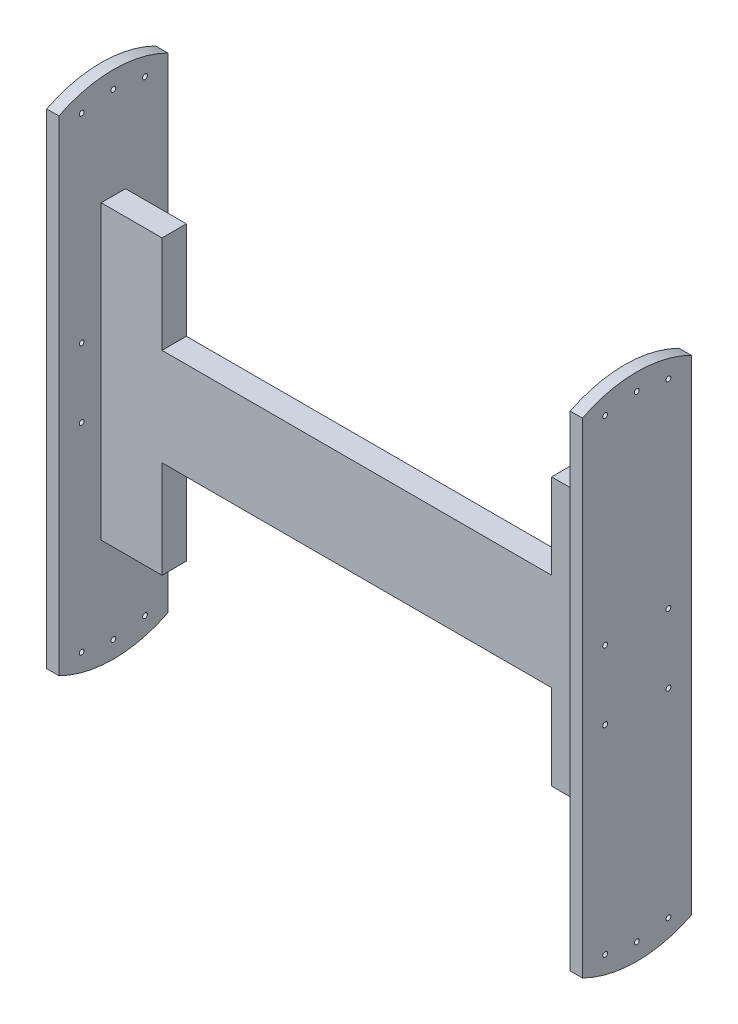
SolidWorks part; units mm, degrees
ref_plane "前视基准面" through (0, 0, 0) normal (0, 0, 1) x (1, 0, 0)
ref_plane "上视基准面" through (0, 0, 0) normal (0, 1, 0) x (1, 0, 0)
ref_plane "右视基准面" through (0, 0, 0) normal (1, 0, 0) x (0, 0, -1)
other "Configuration Table"
sketch "草图1" plane through (0, 0, 0) normal (0, 0, 1) x (1, 0, 0)
  line L1 (0, 0) -> (220, 0)
  line L2 (0, 0) -> (0, 120)
  line L3 (0, 120) -> (220, 120)
  line L4 (220, 0) -> (220, 120)
  dimension "D1" = 220
  dimension "D2" = 120
extrude "凸台-拉伸1" add sketch "草图1" along normal blind 10
sketch "草图2" plane through (0, 0, 10) normal (0, 0, 1) x (1, 0, 0)
  line L0 (0, 60) -> (220, 60) construction
  line L1 (0, 120) -> (0, 0) construction
  line L2 (220, 0) -> (220, 120) construction
  line L3 (30, 120) -> (30, 80)
  line L4 (220, 120) -> (0, 120) construction
  line L5 (30, 80) -> (190, 80)
  line L6 (190, 80) -> (190, 115)
  line L7 (190, 115) -> (220, 115)
  line L8 (190, 5) -> (220, 5)
  line L9 (190, 40) -> (190, 5)
  line L10 (30, 0) -> (30, 40)
  line L11 (30, 40) -> (190, 40)
  line L12 (0, 120) -> (0, 0)
  line L13 (0, 0) -> (220, 0)
  line L14 (220, 0) -> (220, 120)
  line L15 (220, 120) -> (0, 120)
  line L16 (0, 120) -> (0, 0)
  line L17 (0, 0) -> (220, 0)
  line L18 (220, 0) -> (220, 120)
  line L19 (220, 120) -> (0, 120)
  line M11 (0, 0) -> (220, 0)
  line M12 (220, 0) -> (220, 120)
  line M13 (220, 120) -> (0, 120)
  dimension "D1" = 0
  dimension "D2" = 30
  dimension "D3" = 30
  dimension "D4" = 5
  dimension "D5" = 20
extrude "切除-拉伸1" cut sketch "草图2" against normal blind 10 contours L6 L7 L3 L5 M12 M13 | L11 L10 L8 L9 M11 M12
sketch "草图5" plane through (220, 0, 0) normal (1, 0, 0) x (0, 0, -1)
  line L0 (-5, 115) -> (-5, 5) construction
  line L1 (-27.365, 70.4262) -> (-27.365, 159.5738)
  line L2 (90.5429, 60) -> (50, 60) construction
  line L3 (17.365, 70.4262) -> (17.365, 159.5738)
  line L4 (0, 5) -> (0, 115)
  line L5 (0, 115) -> (-10, 115)
  line L6 (-10, 115) -> (-10, 5)
  line L7 (-10, 5) -> (0, 5)
  line L9 (0, 115) -> (-10, 115)
  line L11 (-10, 5) -> (0, 5)
  line L12 (-5, 115) -> (-5, 193.5137) construction
  line L14 (-60, 60) -> (-98.887, 60) construction
  line L17 (0, 5) -> (-10, 5)
  line L18 (17.365, 49.5738) -> (17.365, -39.5738)
  line L19 (-27.365, 49.5738) -> (-27.365, -39.5738)
  line L22 (-27.365, 70.4262) -> (-27.365, 49.5738)
  line L23 (17.365, 70.4262) -> (17.365, 49.5738)
  circle A0 centre (-5, 60) radius 55 construction
  arc A1 (-27.365, 78.4262) -> (17.365, 78.4262) centre (-5, 115) ccw construction
  circle A3 centre (-5, 157.87) radius 1
  circle A4 centre (-18, 155.8514) radius 1
  circle A5 centre (8, 155.8514) radius 1
  arc A6 (17.365, 159.5738) -> (-27.365, 159.5738) centre (-5, 115) ccw
  arc A7 (17.365, 151.5738) -> (-27.365, 151.5738) centre (-5, 115) ccw construction
  circle A8 centre (8, 74.1486) radius 1
  circle A9 centre (-5, 72.13) radius 1
  circle A10 centre (-18, 74.1486) radius 1
  arc A11 (17.365, -31.5738) -> (-27.365, -31.5738) centre (-5, 5) cw construction
  arc A12 (-27.365, 41.5738) -> (17.365, 41.5738) centre (-5, 5) cw construction
  circle A13 centre (-18, 45.8514) radius 1
  circle A14 centre (-5, 47.87) radius 1
  circle A15 centre (8, 45.8514) radius 1
  arc A16 (17.365, -39.5738) -> (-27.365, -39.5738) centre (-5, 5) cw
  circle A17 centre (8, -35.8514) radius 1
  circle A18 centre (-18, -35.8514) radius 1
  circle A19 centre (-5, -37.87) radius 1
  point P6 (-5, 60)
  dimension "D2" = 110
  dimension "D3" = 85.74
  dimension "D6" = 2
  dimension "D7" = 2
  dimension "D8" = 2
  dimension "D5" = 44.73
  dimension "D9" = 13
  dimension "D10" = 13
  dimension "D1" = 0
extrude "凸台-拉伸2" add sketch "草图5" against normal blind 5
ref_plane "基准面1" through (110, 0, 0) normal (1, 0, 0) x (0, 0, -1)
mirror "镜向1" about plane through (110, 0, 0) normal (1, 0, 0) of "凸台-拉伸2"
